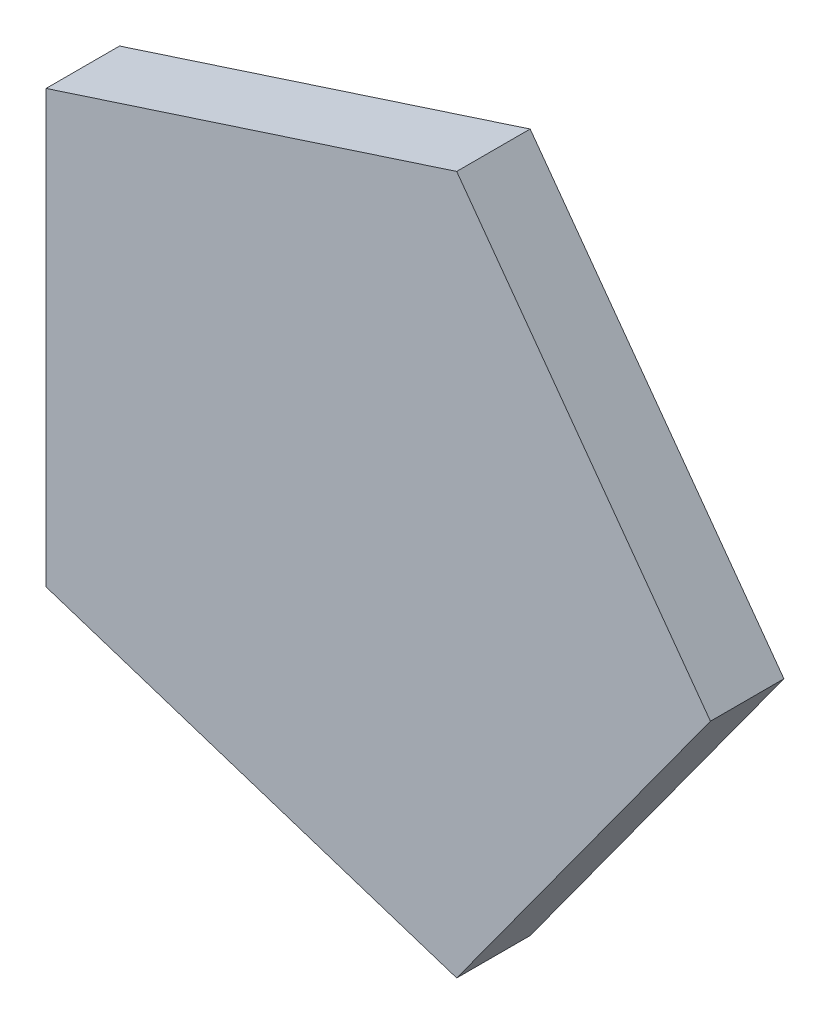
SolidWorks part; units mm, degrees
ref_plane "前视基准面" through (0, 0, 0) normal (0, 0, 1) x (1, 0, 0)
ref_plane "上视基准面" through (0, 0, 0) normal (0, 1, 0) x (1, 0, 0)
ref_plane "右视基准面" through (0, 0, 0) normal (1, 0, 0) x (0, 0, -1)
other "Configuration Table"
sketch "草图1" plane through (0, 0, 0) normal (0, 0, 1) x (1, 0, 0)
  line L1 (100, 0) -> (30.9017, 95.1057)
  line L2 (30.9017, 95.1057) -> (-80.9017, 58.7785)
  line L3 (-80.9017, 58.7785) -> (-80.9017, -58.7785)
  line L4 (-80.9017, -58.7785) -> (30.9017, -95.1057)
  line L5 (30.9017, -95.1057) -> (100, 0)
  circle A0 centre (0, 0) radius 80.9017 construction
extrude "凸台-拉伸1" add sketch "草图1" along normal blind 20
